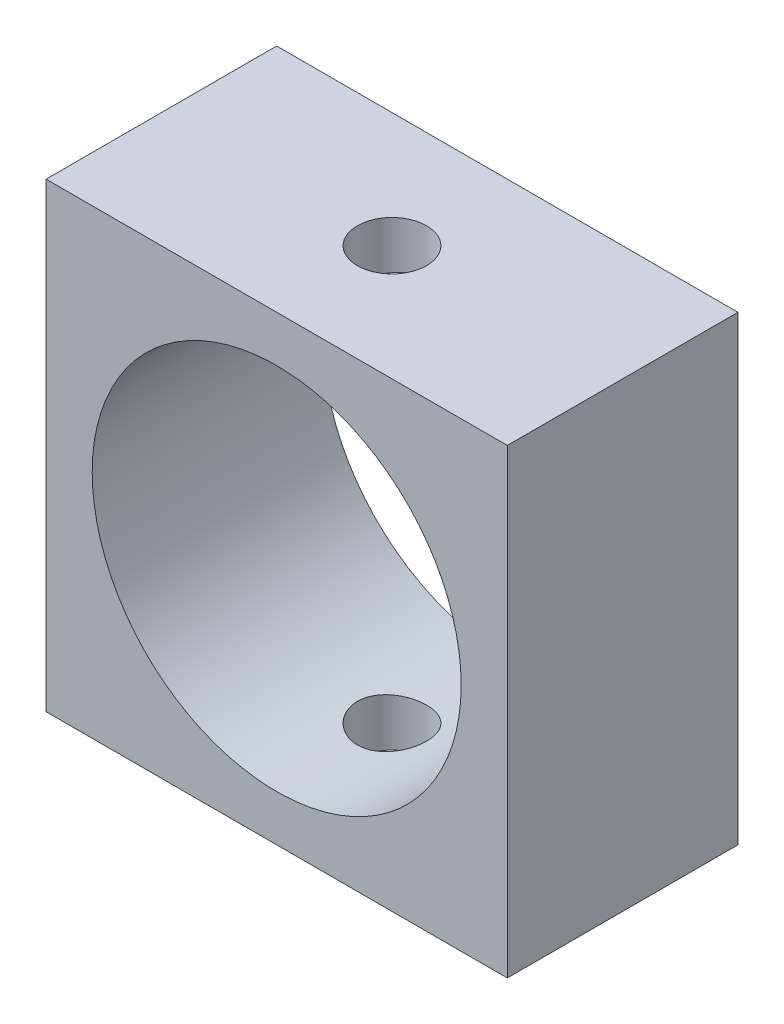
SolidWorks part; units mm, degrees
material "6061 合金"
ref_plane "前视基准面" through (0, 0, 0) normal (0, 0, 1) x (1, 0, 0)
ref_plane "上视基准面" through (0, 0, 0) normal (0, 1, 0) x (1, 0, 0)
ref_plane "右视基准面" through (0, 0, 0) normal (1, 0, 0) x (0, 0, -1)
sketch "草图1" plane through (0, 0, 0) normal (0, 0, 1) x (1, 0, 0)
  line L1 (10, 10) -> (-10, 10)
  line L2 (10, 10) -> (10, -10)
  line L3 (10, -10) -> (-10, -10)
  line L4 (-10, 10) -> (-10, -10)
  line L5 (10, 10) -> (-10, -10) construction
  line L6 (10, -10) -> (-10, 10) construction
  circle A0 centre (0, 0) radius 8
  dimension "D1" = 16
  dimension "D2" = 20
extrude "凸台-拉伸1" add sketch "草图1" along normal blind 10
sketch "草图2" plane through (0, 0, 0) normal (0, 1, 0) x (1, 0, 0)
  line L0 (-10, -5) -> (10, -5) construction
  line L1 (-10, -10) -> (-10, 0) construction
  line L2 (10, -10) -> (10, 0) construction
  circle A0 centre (0, -5) radius 1.5
  dimension "D1" = 3
extrude "切除-拉伸1" cut sketch "草图2" against normal through all both and the other way through all
